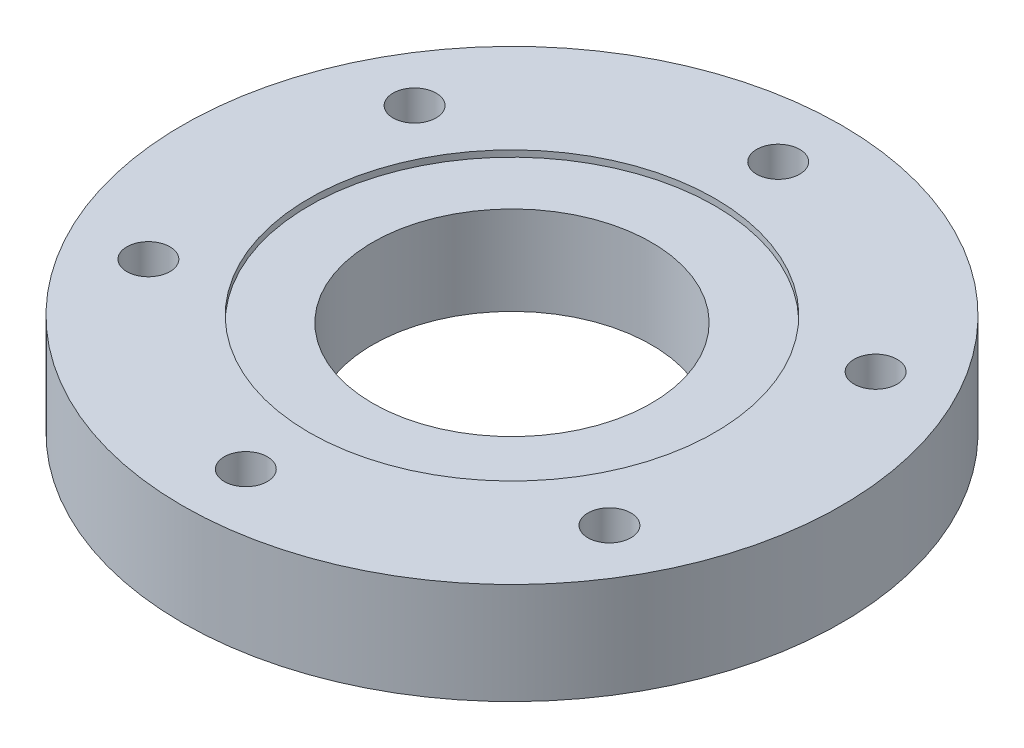
SolidWorks part; units mm, degrees
ref_plane "前视基准面" through (0, 0, 0) normal (0, 0, 1) x (1, 0, 0)
ref_plane "上视基准面" through (0, 0, 0) normal (0, 1, 0) x (1, 0, 0)
ref_plane "右视基准面" through (0, 0, 0) normal (1, 0, 0) x (0, 0, -1)
other "Configuration Table"
sketch "草图1" plane through (0, 0, 0) normal (0, 1, 0) x (1, 0, 0)
  line L0 (0, 42.5475) -> (0, -34.1312) construction
  line L1 (0, 0) -> (0, 21) construction
  line L2 (0, 0) -> (18.1865, 10.5) construction
  circle A0 centre (0, 0) radius 26
  circle A1 centre (0, 0) radius 21 construction
  circle A2 centre (0, 21) radius 1.7
  circle A3 centre (18.1865, 10.5) radius 1.7
  circle A4 centre (18.1865, -10.5) radius 1.7
  circle A5 centre (0, -21) radius 1.7
  circle A6 centre (-18.1865, -10.5) radius 1.7
  circle A7 centre (-18.1865, 10.5) radius 1.7
  circle A8 centre (0, 0) radius 16
  dimension "D1" = 52
  dimension "D2" = 42
  dimension "D3" = 3.4
  dimension "D6" = 32
  dimension "D5" = 60
  dimension "D4" = 6
extrude "凸台-拉伸1" add sketch "草图1" along normal blind 8
sketch "草图2" plane through (0, 0, 0) normal (0, 1, 0) x (1, 0, 0)
  line L0 (0, 0) -> (0, 21) construction
  line L1 (0, 0) -> (18.1865, 10.5) construction
  circle A0 centre (0, 21) radius 3.25
  circle A1 centre (18.1865, 10.5) radius 3.25
  circle A2 centre (18.1865, -10.5) radius 3.25
  circle A3 centre (0, -21) radius 3.25
  circle A4 centre (-18.1865, -10.5) radius 3.25
  circle A5 centre (-18.1865, 10.5) radius 3.25
  dimension "D1" = 6.5
  dimension "D3" = 60
  dimension "D4" = 21
  dimension "D2" = 6
extrude "切除-拉伸1" cut sketch "草图2" along normal blind 3.3
sketch "草图3" plane through (0, 0, 0) normal (0, 1, 0) x (1, 0, 0)
  circle A0 centre (0, 0) radius 11
  circle A1 centre (0, 0) radius 16
  circle A2 centre (0, 0) radius 16 construction
  dimension "D1" = 22
extrude "凸台-拉伸2" add sketch "草图3" along normal blind 7 from offset 0.5
